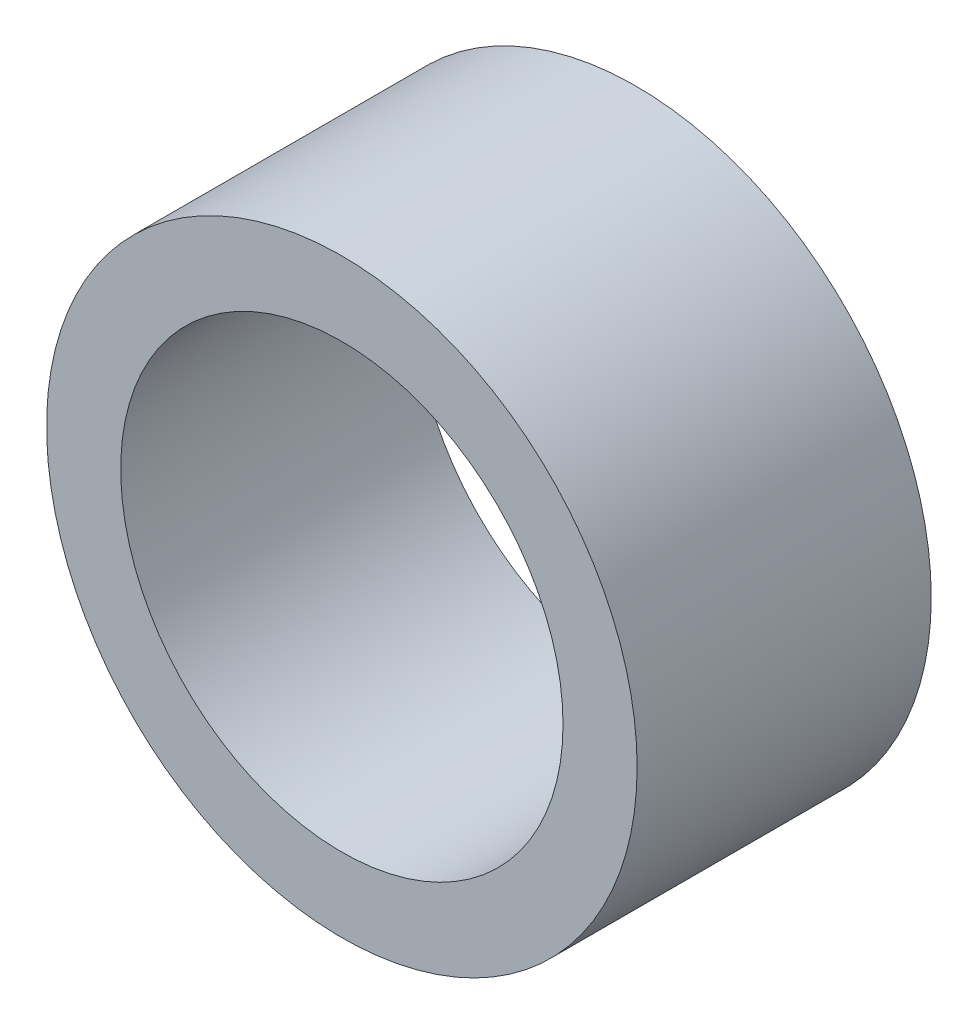
SolidWorks part; units mm, degrees
ref_plane "Front Plane" through (0, 0, 0) normal (0, 0, 1) x (1, 0, 0)
ref_plane "Top Plane" through (0, 0, 0) normal (0, 1, 0) x (1, 0, 0)
ref_plane "Right Plane" through (0, 0, 0) normal (1, 0, 0) x (0, 0, -1)
sketch "Sketch1" plane through (0, 0, 0) normal (0, 0, 1) x (1, 0, 0)
  circle A0 centre (0, 0) radius 6.3754
  circle A1 centre (0, 0) radius 4.7752
  dimension "D1" = 12.7508
  dimension "ID" = 9.5504
extrude "Extrude1" add sketch "Sketch1" along normal mid plane 6.35
sketch "Sketch2" plane through (0, 0, 0) normal (1, 0, 0) x (0, 0, -1)
  line L0 (-3.175, -4.7752) -> (3.175, -4.7752) construction
  line L3 (3.175, 4.7752) -> (-3.175, 4.7752) construction
  line L5 (-3.175, -4.7752) -> (3.175, -4.7752)
  line L6 (3.175, 4.7752) -> (-3.175, 4.7752)
sketch "Sketch4" plane through (0, 0, 3.175) normal (0, 0, 1) x (1, 0, 0)
  line L0 (0, 0) -> (-3.3766, 3.3766)
  line L1 (0, -7.8791) -> (0, 7.8791) construction
  circle A0 centre (0, 0) radius 4.7752 construction
  dimension "D1" = 45
